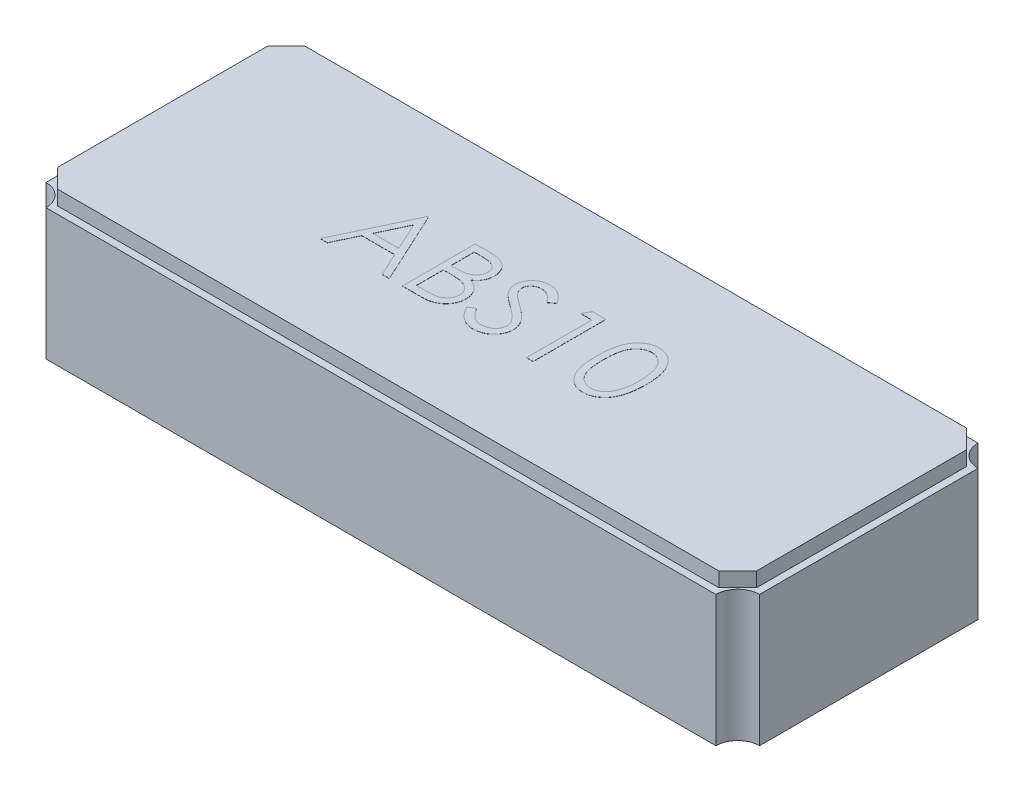
SolidWorks part; units mm, degrees
ref_plane "Front Plane" through (0, 0, 0) normal (0, 0, 1) x (1, 0, 0)
ref_plane "Top Plane" through (0, 0, 0) normal (0, 1, 0) x (1, 0, 0)
ref_plane "Right Plane" through (0, 0, 0) normal (1, 0, 0) x (0, 0, -1)
sketch "Sketch1" plane through (0, 0, 0) normal (0, 1, 0) x (1, 0, 0)
  line L1 (-2.3, -0.9) -> (2.3, -0.9)
  line L2 (-2.45, -0.75) -> (-2.45, 0.75)
  line L3 (-2.3, 0.9) -> (2.3, 0.9)
  line L4 (2.45, -0.75) -> (2.45, 0.75)
  line L5 (-2.3092, -0.8483) -> (2.3092, 0.8483) construction
  line L6 (-2.3092, 0.8483) -> (2.3092, -0.8483) construction
  arc A0 (-2.45, 0.75) -> (-2.3, 0.9) centre (-2.45, 0.9) ccw
  arc A1 (2.3, 0.9) -> (2.45, 0.75) centre (2.45, 0.9) ccw
  arc A2 (-2.3, -0.9) -> (-2.45, -0.75) centre (-2.45, -0.9) ccw
  arc A3 (2.45, -0.75) -> (2.3, -0.9) centre (2.45, -0.9) ccw
  point P0 (0, 0)
  dimension "D3" = 2
  dimension "D4" = 2
extrude "Boss-Extrude1" add sketch "Sketch1" along normal blind 0.9
sketch "Sketch2" plane through (0, 0.9, 0) normal (0, 1, 0) x (1, 0, 0)
  line L0 (2.27, 0.85) -> (2.4, 0.72)
  line L1 (-2.27, -0.85) -> (2.27, -0.85)
  line L2 (-2.4, -0.72) -> (-2.4, 0.72)
  line L3 (-2.27, 0.85) -> (2.27, 0.85)
  line L4 (2.4, -0.72) -> (2.4, 0.72)
  line L5 (-2.4, -0.85) -> (2.4, 0.85) construction
  line L6 (-2.4, 0.85) -> (2.4, -0.85) construction
  line L7 (2.27, -0.85) -> (2.4, -0.72)
  line L8 (-2.4, -0.72) -> (-2.27, -0.85)
  line L9 (-2.4, 0.72) -> (-2.27, 0.85)
  point P0 (0, 0)
  dimension "D1" = 4.8
  dimension "D2" = 1.7
  dimension "D3" = 0.13
  dimension "D4" = 45
  dimension "D5" = 0.13
  dimension "D6" = 45
  dimension "D7" = 0.13
  dimension "D8" = 45
  dimension "D9" = 0.13
  dimension "D10" = 45
extrude "Boss-Extrude2" add sketch "Sketch2" along normal blind 0.1
sketch "Sketch3" plane through (0, 0, 0) normal (0, -1, 0) x (1, 0, 0)
  line L0 (0, 0.9) -> (0, -0.9) construction
  line L1 (-2.3, 0.9) -> (2.3, 0.9) construction
  line L2 (2.3, -0.9) -> (-2.3, -0.9) construction
  line L4 (-2.2, -0.8) -> (-1.6, -0.8)
  line L5 (-2.35, -0.65) -> (-2.35, 0.65)
  line L6 (-2.2, 0.8) -> (-1.6, 0.8)
  line L7 (-1.6, -0.8) -> (-1.6, 0.8)
  line L8 (1.6, -0.8) -> (1.6, 0.8)
  line L9 (2.2, 0.8) -> (1.6, 0.8)
  line L10 (2.35, -0.65) -> (2.35, 0.65)
  line L11 (2.2, -0.8) -> (1.6, -0.8)
  arc A0 (-2.35, 0.65) -> (-2.2, 0.8) centre (-2.35, 0.8) ccw
  arc A1 (-2.2, -0.8) -> (-2.35, -0.65) centre (-2.35, -0.8) ccw
  arc A2 (2.2, -0.8) -> (2.35, -0.65) centre (2.35, -0.8) cw
  arc A3 (2.35, 0.65) -> (2.2, 0.8) centre (2.35, 0.8) cw
  dimension "D1" = 0.75
  dimension "D2" = 1.6
  dimension "D3" = 0.1
  dimension "D4" = 1.6
extrude "Boss-Extrude3" add sketch "Sketch3" along normal blind 0.001
sketch "Sketch4" plane through (0, 1, 0) normal (0, 1, 0) x (1, 0, 0)
  text T0 "ABS10" font "Century Gothic" height 0.5
extrude "Boss-Extrude4" add sketch "Sketch4" along normal blind 0.001
